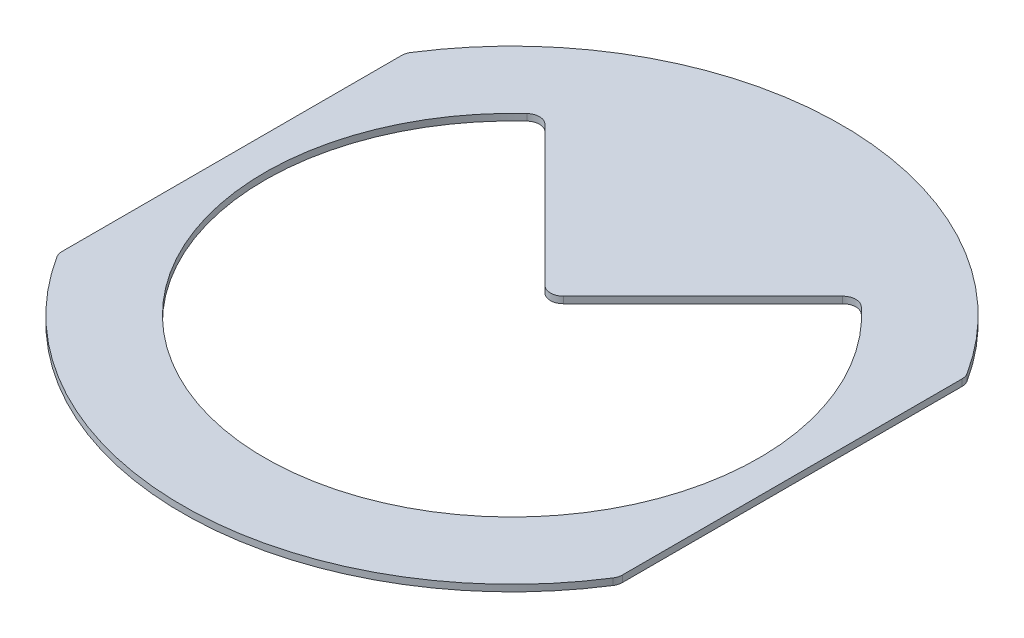
SolidWorks part; units mm, degrees
ref_plane "Front" through (0, 0, 0) normal (0, 0, 1) x (1, 0, 0)
ref_plane "Top" through (0, 0, 0) normal (0, 1, 0) x (1, 0, 0)
ref_plane "Right" through (0, 0, 0) normal (1, 0, 0) x (0, 0, -1)
sketch "Sketch1" plane through (0, 0, 0) normal (0, 1, 0) x (1, 0, 0)
  line L0 (-42.5, 26.3391) -> (-42.5, -26.3391)
  line L1 (0, 55.799) -> (0, -56.3751) construction
  line L2 (42.5, 26.3391) -> (42.5, -26.3391)
  line L3 (-23.8984, 28.8984) -> (0, 5)
  line L4 (0, 5) -> (23.8984, 28.8984)
  arc A0 (-42.5, -26.3391) -> (42.5, -26.3391) centre (0, 0) ccw
  arc A1 (42.5, 26.3391) -> (-42.5, 26.3391) centre (0, 0) ccw
  arc A2 (-23.8984, 28.8984) -> (23.8984, 28.8984) centre (0, 0) ccw
  dimension "D1" = 100
  dimension "D3" = 75
  dimension "D2" = 85
  dimension "D4" = 90
  dimension "D5" = 5
extrude "Boss-Extrude1" add sketch "Sketch1" along normal blind 1
fillet "Fillet1" radius 2 7 edges at (-23.8984, 0.5, -28.8984) (23.8984, 0.5, -28.8984) (42.5, 0.5, -26.3391) (42.5, 0.5, 26.3391) (-42.5, 0.5, 26.3391) (-42.5, 0.5, -26.3391) (0, 0.5, -5)
